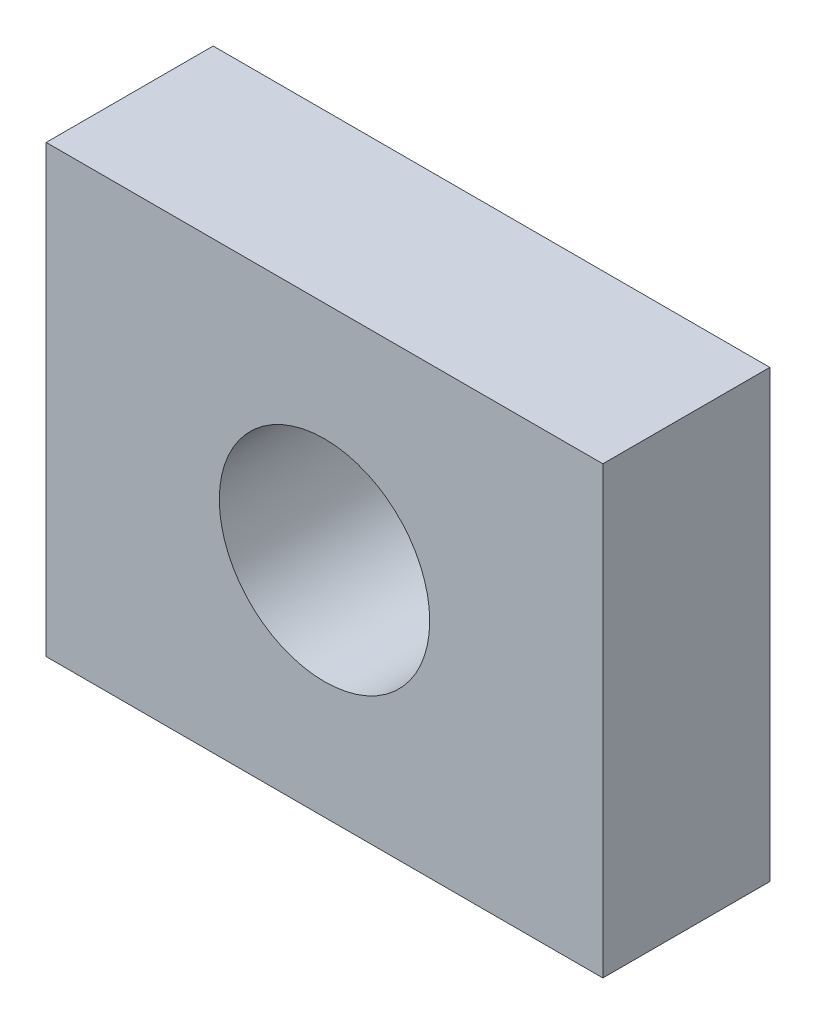
SolidWorks part; units mm, degrees
ref_plane "Front Plane" through (0, 0, 0) normal (0, 0, 1) x (1, 0, 0)
ref_plane "Top Plane" through (0, 0, 0) normal (0, 1, 0) x (1, 0, 0)
ref_plane "Right Plane" through (0, 0, 0) normal (1, 0, 0) x (0, 0, -1)
sketch "Sketch1" plane through (0, 0, 0) normal (0, 0, 1) x (1, 0, 0)
  line L1 (-15.875, -12.7) -> (15.875, -12.7)
  line L2 (-15.875, -12.7) -> (-15.875, 12.7)
  line L3 (-15.875, 12.7) -> (15.875, 12.7)
  line L4 (15.875, -12.7) -> (15.875, 12.7)
  line L5 (-15.875, -12.7) -> (15.875, 12.7) construction
  line L6 (-15.875, 12.7) -> (15.875, -12.7) construction
  circle A0 centre (0, 0) radius 6
  point P0 (0, 0)
  dimension "D3" = 12
  dimension "D1" = 31.75
  dimension "D2" = 25.4
extrude "Boss-Extrude1" add sketch "Sketch1" along normal blind 9.525
